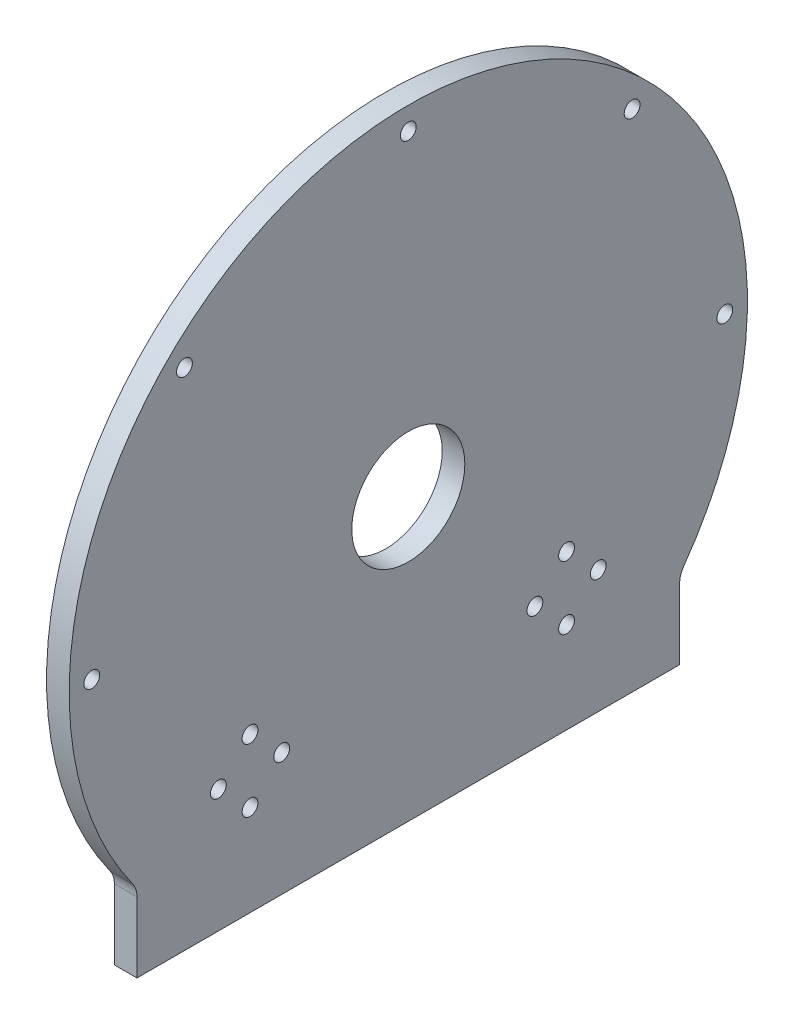
SolidWorks part; units mm, degrees
material "普通碳钢"
ref_plane "前视" through (0, 0, 0) normal (0, 0, 1) x (1, 0, 0)
ref_plane "上视" through (0, 0, 0) normal (0, 1, 0) x (1, 0, 0)
ref_plane "右视" through (0, 0, 0) normal (1, 0, 0) x (0, 0, -1)
sketch "草图1" plane through (0, 0, 0) normal (1, 0, 0) x (0, 0, -1)
  line L0 (0, 0) -> (0, 160)
  line L1 (0, 0) -> (120, 0)
  line L2 (120, 0) -> (120, 160)
  line L3 (60, 280) -> (60, 0) construction
  line L4 (39, 81) -> (39, 59) construction
  line L5 (40.5, 81) -> (40.5, 59)
  line L6 (37.5, 81) -> (37.5, 59)
  line L7 (81, 81) -> (81, 59) construction
  line L8 (79.5, 81) -> (79.5, 59)
  line L9 (82.5, 81) -> (82.5, 59)
  line L10 (60, 205) -> (6.967, 258.033) construction
  line L11 (60, 205) -> (113.033, 258.033) construction
  line L12 (-15, 205) -> (135, 205) construction
  line L13 (115, 5) -> (115, 161.6987) construction
  line L14 (5, 5) -> (115, 5) construction
  line L15 (5, 5) -> (5, 161.6987) construction
  arc A0 (0, 160) -> (120, 160) centre (60, 205) cw
  circle A1 centre (60, 205) radius 12.5
  circle A2 centre (25, 170) radius 7 construction
  circle A3 centre (95, 170) radius 7 construction
  circle A4 centre (25, 177) radius 1.75
  circle A5 centre (32, 170) radius 1.75
  circle A6 centre (25, 163) radius 1.75
  circle A7 centre (18, 170) radius 1.75
  circle A8 centre (95, 177) radius 1.75
  circle A9 centre (102, 170) radius 1.75
  circle A10 centre (95, 163) radius 1.75
  circle A11 centre (88, 170) radius 1.75
  circle A12 centre (39, 140) radius 1.75
  circle A13 centre (81, 140) radius 1.75
  arc A14 (40.5, 81) -> (37.5, 81) centre (39, 81) ccw
  arc A15 (37.5, 59) -> (40.5, 59) centre (39, 59) ccw
  arc A16 (79.5, 81) -> (82.5, 81) centre (81, 81) cw
  arc A17 (82.5, 59) -> (79.5, 59) centre (81, 59) cw
  circle A18 centre (60, 275) radius 1.75
  circle A19 centre (-10, 205) radius 1.75
  circle A20 centre (130, 205) radius 1.75
  circle A21 centre (10.5025, 254.4975) radius 1.75
  circle A22 centre (109.4975, 254.4975) radius 1.75
  arc A23 (5, 161.6987) -> (115, 161.6987) centre (60, 205) cw construction
  circle A24 centre (5, 5) radius 1.75
  circle A25 centre (115, 5) radius 1.75
  circle A26 centre (5, 120) radius 1.75
  circle A27 centre (115, 120) radius 1.75
  point P35 (39, 70)
  point P42 (81, 70)
  dimension "D2" = 75
  dimension "D4" = 25
  dimension "D5" = 14
  dimension "D7" = 3.5
  dimension "D8" = 170
  dimension "D9" = 3.5
  dimension "D14" = 3.5
  dimension "D15" = 115
  dimension "D16" = 140
  dimension "D17" = 25
  dimension "D18" = 1.5
  dimension "D1" = 120
  dimension "D3" = 280
  dimension "D6" = 70
  dimension "D10" = 42
  dimension "D11" = 45
  dimension "D12" = 90
  dimension "D19" = 70
  dimension "D13" = 5
extrude "凸台-拉伸1" add sketch "草图1" along normal blind 5
fillet "圆角1" radius 5 4 edges at (2.5, 160, 0) (2.5, 160, -120) (2.5, 0, -120) (2.5, 0, 0)
sketch "草图2" plane through (5, 0, 0) normal (1, 0, 0) x (0, 0, -1)
  line L0 (120, 5) -> (120, 158.3631) construction
  line L1 (44, 101) -> (60, 101) construction
  line L2 (44, 101) -> (44, 65) construction
  line L3 (44, 65) -> (60, 65) construction
  line L4 (60, 101) -> (60, 65) construction
  line L5 (5, 0) -> (115, 0) construction
  circle A1 centre (60, 101) radius 1.1
  circle A2 centre (60, 65) radius 1.1
  circle A3 centre (44, 65) radius 1.1
  circle A4 centre (44, 101) radius 1.1
  dimension "D4" = 2.2
  dimension "D1" = 36
  dimension "D2" = 16
  dimension "D3" = 65
  dimension "D5" = 60
sketch "草图3" plane through (0, 0, 0) normal (-1, 0, 0) x (0, 0, 1)
  line L0 (-20, 48.5) -> (-30, 48.5) construction
  line L1 (-20, 46.75) -> (-30, 46.75)
  line L2 (-20, 50.25) -> (-30, 50.25)
  line L3 (-90, 48.5) -> (-100, 48.5) construction
  line L4 (-90, 46.75) -> (-100, 46.75)
  line L5 (-90, 50.25) -> (-100, 50.25)
  line L6 (-20, 10) -> (-30, 10) construction
  line L7 (-20, 8.25) -> (-30, 8.25)
  line L8 (-20, 11.75) -> (-30, 11.75)
  line L9 (-90, 10) -> (-100, 10) construction
  line L10 (-90, 8.25) -> (-100, 8.25)
  line L11 (-90, 11.75) -> (-100, 11.75)
  line L12 (-60, 0) -> (-60, 280) construction
  line L13 (-25, 48.5) -> (-95, 48.5) construction
  line L14 (-25, 48.5) -> (-25, 10) construction
  line L15 (-25, 10) -> (-95, 10) construction
  line L16 (-95, 48.5) -> (-95, 10) construction
  line L17 (-5, 0) -> (-115, 0) construction
  circle A0 centre (-45.8181, 127.4583) radius 1.1
  circle A1 centre (-61.8181, 127.4583) radius 1.1
  circle A2 centre (-45.8181, 91.4583) radius 1.1
  circle A3 centre (-61.8181, 91.4583) radius 1.1
  arc A4 (-20, 46.75) -> (-20, 50.25) centre (-20, 48.5) ccw
  arc A5 (-30, 50.25) -> (-30, 46.75) centre (-30, 48.5) ccw
  arc A6 (-90, 46.75) -> (-90, 50.25) centre (-90, 48.5) ccw
  arc A7 (-100, 50.25) -> (-100, 46.75) centre (-100, 48.5) ccw
  arc A8 (-20, 8.25) -> (-20, 11.75) centre (-20, 10) ccw
  arc A9 (-30, 11.75) -> (-30, 8.25) centre (-30, 10) ccw
  arc A10 (-90, 8.25) -> (-90, 11.75) centre (-90, 10) ccw
  arc A11 (-100, 11.75) -> (-100, 8.25) centre (-100, 10) ccw
  arc A12 (0.9375, 161.2779) -> (-120.9375, 161.2779) centre (-60, 205) ccw construction
  point P16 (-25, 48.5)
  point P22 (-95, 48.5)
  point P29 (-25, 10)
  point P36 (-95, 10)
  dimension "D1" = 2.2
  dimension "D2" = 2.2
  dimension "D3" = 3.5
  dimension "D4" = 10
  dimension "D5" = 35
  dimension "D6" = 70
  dimension "D7" = 10
extrude "切除-拉伸2" cut sketch "草图3" against normal blind 10
sketch "草图4" plane through (0, 0, 0) normal (-1, 0, 0) x (0, 0, 1)
  line L0 (-60, 0) -> (-60, 280) construction
  line L1 (-5, 0) -> (-115, 0) construction
  line L2 (-81, 140) -> (-39, 140) construction
  circle A0 centre (-16.1189, 88.7406) radius 1.5
  circle A1 centre (-16.1189, 64.2406) radius 1.5
  circle A2 centre (-94, 140) radius 1.5
  circle A3 centre (-26, 140) radius 1.5
  arc A4 (0.9375, 161.2779) -> (-120.9375, 161.2779) centre (-60, 205) ccw construction
  circle A5 centre (-94, 82) radius 1.5
  circle A6 centre (-26, 82) radius 1.5
  dimension "D1" = 3
  dimension "D2" = 3
  dimension "D3" = 3
  dimension "D5" = 58
  dimension "D4" = 68
extrude "切除-拉伸3" cut sketch "草图4" against normal blind 10
sketch "Sketch1" plane through (0, 0, 0) normal (-1, 0, 0) x (0, 0, 1)
  line L0 (-120, 142.8226) -> (0, 142.8226)
  line L1 (-120, 5) -> (-120, 158.3631) construction
  line L2 (0, 158.3631) -> (0, 5) construction
extrude "Extrude2" cut sketch "Sketch1" against normal through all and the other way through all flip side to cut
